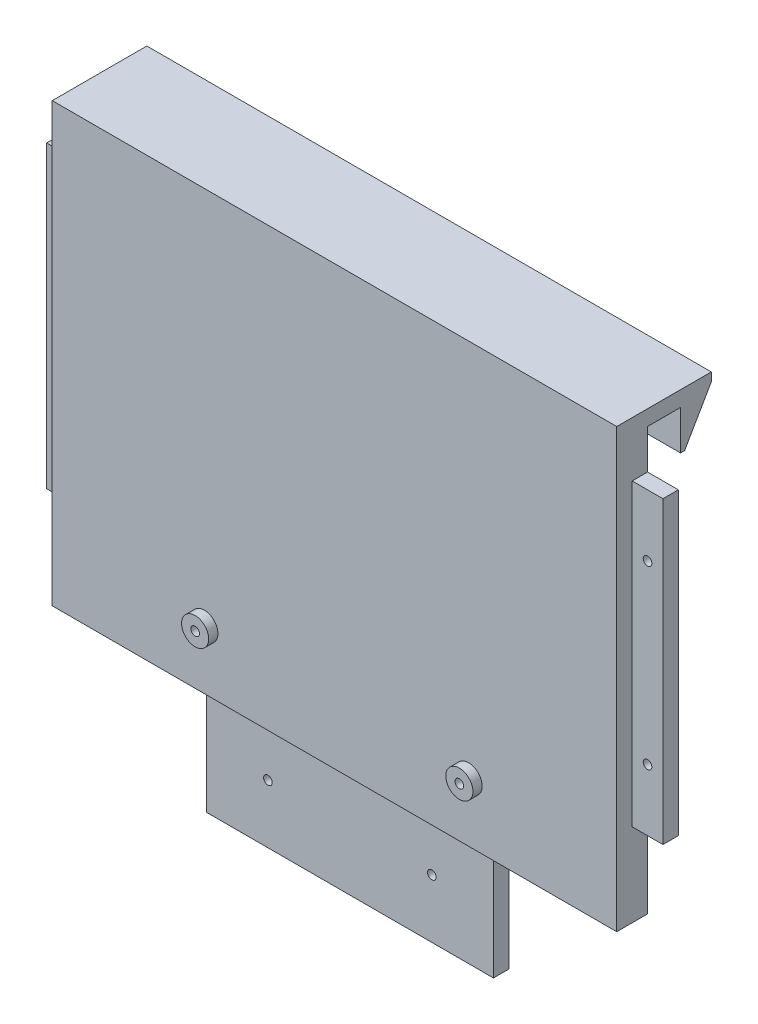
SolidWorks part; units mm, degrees
ref_plane "Alzado" through (0, 0, 0) normal (0, 0, 1) x (1, 0, 0)
ref_plane "Planta" through (0, 0, 0) normal (0, 1, 0) x (1, 0, 0)
ref_plane "Vista lateral" through (0, 0, 0) normal (1, 0, 0) x (0, 0, -1)
sketch "Croquis1" plane through (0, 0, 0) normal (0, 0, 1) x (1, 0, 0)
  line L1 (0, 0) -> (180, 0)
  line L2 (0, 0) -> (0, 180)
  line L3 (0, 180) -> (180, 180)
  line L4 (180, 0) -> (180, 180)
  dimension "D1" = 180
extrude "Saliente-Extruir1" add sketch "Croquis1" along normal blind 30.7
sketch "Croquis2" plane through (0, 0, 0) normal (0, 0, -1) x (-1, 0, 0)
  line L0 (-180, 0) -> (-180, 180) construction
  line L1 (-180, 162.21) -> (0, 162.21)
  line L2 (-180, 162.21) -> (-180, 0)
  line L3 (-180, 0) -> (0, 0)
  line L4 (0, 162.21) -> (0, 0)
  line L5 (-180, 180) -> (0, 180) construction
  dimension "D1" = 17.79
extrude "Cortar-Extruir1" cut sketch "Croquis2" against normal blind 20.7
sketch "Croquis3" plane through (0, 0, 0) normal (-1, 0, 0) x (0, 0, 1)
  line L0 (30.7, 180) -> (0, 180) construction
  line L1 (20.7, 162.21) -> (10, 162.21)
  line L2 (20.7, 162.21) -> (20.7, 175)
  line L3 (20.7, 175) -> (10, 175)
  line L4 (10, 162.21) -> (10, 175)
  dimension "D1" = 5
  dimension "D2" = 10.7
extrude "Cortar-Extruir2" cut sketch "Croquis3" against normal blind 274.7
sketch "Croquis4" plane through (180, 0, 0) normal (1, 0, 0) x (0, 0, -1)
  line L8 (-20.7, 0) -> (-20.7, 175)
  line L9 (-20.7, 175) -> (-10, 175)
  line L10 (-10, 175) -> (-10, 162.21)
  line L11 (-10, 162.21) -> (0, 162.21)
  line L12 (0, 162.21) -> (0, 180)
  line L13 (0, 180) -> (-30.7, 180)
  line L14 (-30.7, 180) -> (-30.7, 0)
  line L15 (-30.7, 0) -> (-20.7, 0)
  line L16 (-20.7, 0) -> (-20.7, 175)
  line L17 (-20.7, 175) -> (-10, 175)
  line L18 (-10, 175) -> (-10, 162.21)
  line L19 (-10, 162.21) -> (0, 162.21)
  line L20 (0, 162.21) -> (0, 180)
  line L21 (0, 180) -> (-30.7, 180)
  line L22 (-30.7, 180) -> (-30.7, 0)
  line L23 (-30.7, 0) -> (-20.7, 0)
  dimension "D1" = 0
extrude "Saliente-Extruir2" add sketch "Croquis4" along normal blind 20
sketch "Croquis5" plane through (0, 0, 30.7) normal (0, 0, 1) x (1, 0, 0)
  line L0 (190, 180) -> (190, 38) construction
  line L1 (0, 0) -> (6.8, 0)
  line L2 (0, 0) -> (0, 65)
  line L3 (0, 65) -> (6.8, 65)
  line L4 (6.8, 38) -> (6.8, 65)
  line L5 (200, 0) -> (190, 0)
  line L6 (200, 0) -> (200, 65)
  line L7 (200, 65) -> (190, 65)
  line L8 (190, 38) -> (190, 65)
  line L9 (200, 180) -> (0, 180) construction
  line L10 (200, 162.21) -> (190, 162.21)
  line L11 (200, 162.21) -> (200, 180)
  line L12 (200, 180) -> (190, 180)
  line L13 (190, 162.21) -> (190, 180)
  line L14 (370, 180) -> (190, 180) construction
  line L15 (6.8, 38) -> (6.8, 180) construction
  line L16 (0, 162.21) -> (6.8, 162.21)
  line L17 (0, 162.21) -> (0, 180)
  line L18 (0, 180) -> (6.8, 180)
  line L19 (6.8, 162.21) -> (6.8, 180)
  line L20 (0, 0) -> (200, 0) construction
  line L21 (190, 38) -> (6.8, 38) construction
  line L22 (190, 0) -> (145, 0)
  line L24 (190, 38) -> (145, 38)
  line L25 (145, 0) -> (145, 38)
  line L27 (6.8, 0) -> (51.8, 0)
  line L29 (6.8, 38) -> (51.8, 38)
  line L30 (51.8, 0) -> (51.8, 38)
  dimension "D1" = 65
  dimension "D2" = 65
  dimension "D3" = 6.8
  dimension "D4" = 10
  dimension "D5" = 45
  dimension "D6" = 45
extrude "Cortar-Extruir3" cut sketch "Croquis5" against normal blind 30.7
sketch "Croquis6" plane through (0, 0, 30.7) normal (0, 0, 1) x (1, 0, 0)
  line L0 (6.8, 65) -> (0, 65) construction
  line L1 (0, 65) -> (6.8, 65)
  line L2 (0, 65) -> (0, 162.21)
  line L3 (0, 162.21) -> (6.8, 162.21)
  line L4 (6.8, 65) -> (6.8, 162.21)
  line L6 (200, 65) -> (190, 65)
  line L7 (200, 65) -> (200, 162.21)
  line L8 (200, 162.21) -> (190, 162.21)
  line L9 (190, 65) -> (190, 162.21)
  line L10 (145, 0) -> (51.8, 0)
  line L11 (145, 0) -> (145, 38)
  line L12 (145, 38) -> (51.8, 38)
  line L13 (51.8, 0) -> (51.8, 38)
extrude "Cortar-Extruir4" cut sketch "Croquis6" against normal blind 5
chamfer "Chaflán1" distance 15 angle 30 1 edges at (98.4, 162.21, 0)
sketch "Croquis7" plane through (0, 0, 30.7) normal (0, 0, 1) x (1, 0, 0)
  line L0 (0, 65) -> (6.8, 65) construction
  line L1 (6.8, 162.21) -> (0, 162.21) construction
  circle A0 centre (125, 19) radius 1.4
  circle A1 centre (71.8, 19) radius 1.4
  circle A2 centre (195, 85) radius 1.4
  circle A3 centre (195, 142.21) radius 1.4
  circle A4 centre (3.4, 142.21) radius 1.4
  circle A5 centre (3.4, 85) radius 1.4
  point P20 (0, 0)
  point P21 (3.4, 65)
  dimension "D3" = 2.8
  dimension "D1" = 20
  dimension "D2" = 20
extrude "Cortar-Extruir5" cut sketch "Croquis7" against normal blind 20
sketch "Croquis8" plane through (0, 0, 30.7) normal (0, 0, 1) x (1, 0, 0)
  circle A0 centre (56.17, 57.07) radius 4.4
  circle A1 centre (56.17, 57.07) radius 1.4
  circle A2 centre (141.93, 57.07) radius 1.4
  circle A3 centre (141.93, 57.07) radius 4.4
extrude "Saliente-Extruir3" add sketch "Croquis8" along normal blind 3
